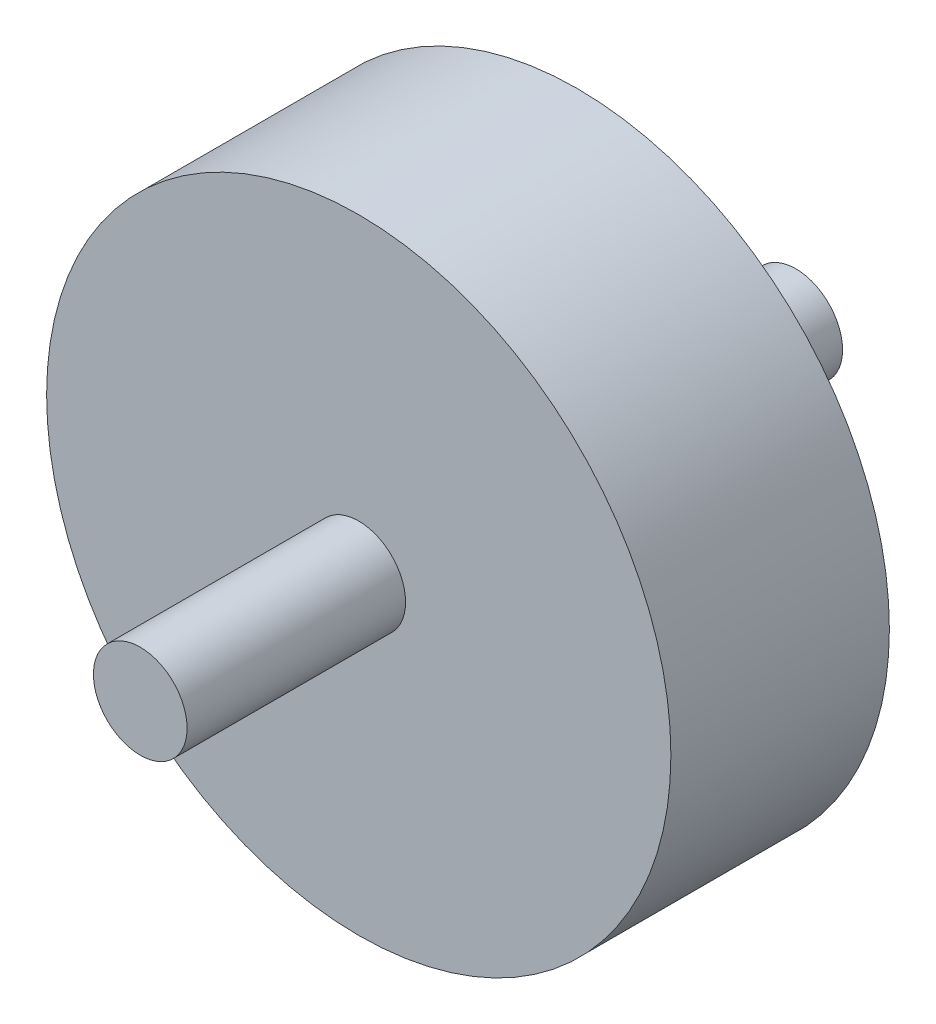
SolidWorks part; units mm, degrees
ref_plane "Front Plane" through (0, 0, 0) normal (0, 0, 1) x (1, 0, 0)
ref_plane "Top Plane" through (0, 0, 0) normal (0, 1, 0) x (1, 0, 0)
ref_plane "Right Plane" through (0, 0, 0) normal (1, 0, 0) x (0, 0, -1)
sketch "Sketch1" plane through (0, 0, 0) normal (0, 0, 1) x (1, 0, 0)
  line L0 (-2795.8507, 0) -> (2529.5792, 0) construction
  line L1 (0, 1327.4417) -> (0, -1589.7975) construction
  circle A0 centre (0, 0) radius 50
  dimension "D1" = 100
extrude "Boss-Extrude3" add sketch "Sketch1" along normal blind 35
sketch "Sketch3" plane through (0, 0, 35) normal (0, 0, 1) x (1, 0, 0)
  circle A0 centre (0, 0) radius 7.5
  dimension "D1" = 15
extrude "Boss-Extrude4" add sketch "Sketch3" along normal blind 35 and the other way blind 70
